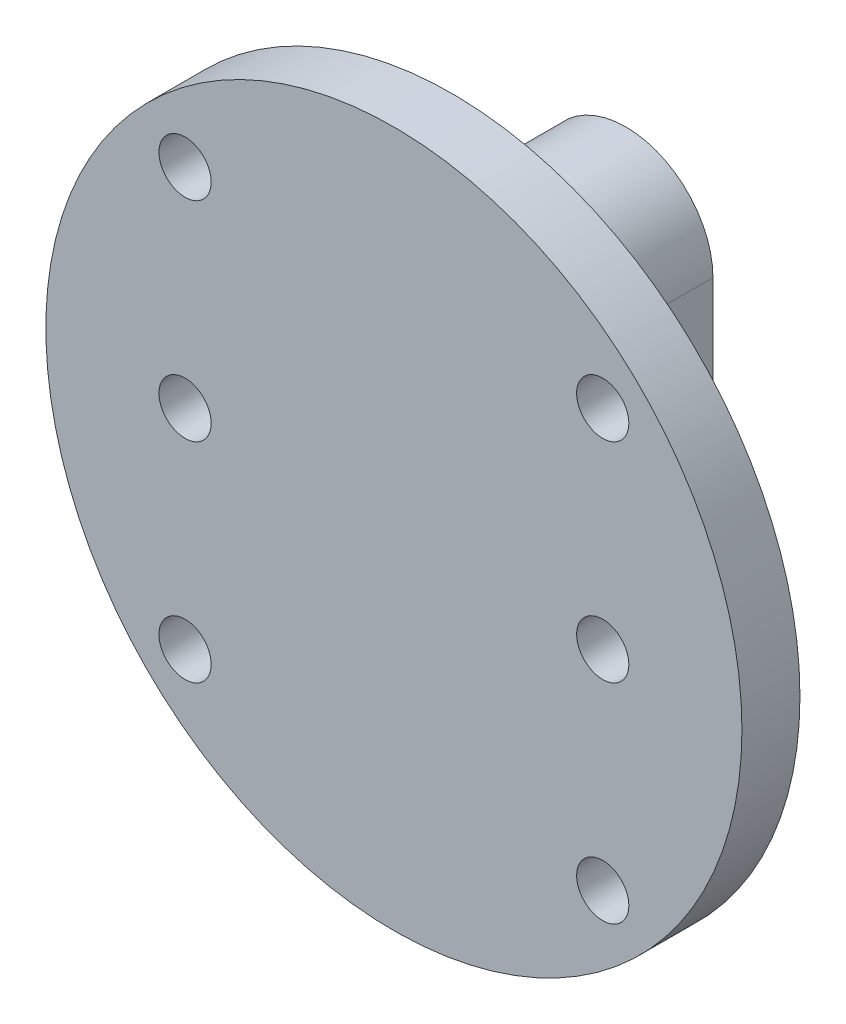
SolidWorks part; units mm, degrees
ref_plane "Plan de face" through (0, 0, 0) normal (0, 0, 1) x (1, 0, 0)
ref_plane "Plan de dessus" through (0, 0, 0) normal (0, 1, 0) x (1, 0, 0)
ref_plane "Plan de droite" through (0, 0, 0) normal (1, 0, 0) x (0, 0, -1)
sketch "Esquisse1" plane through (0, 0, 0) normal (0, 0, 1) x (1, 0, 0)
  line L0 (18, 0) -> (-18, 0) construction
  line L1 (18, 18) -> (-18, 18) construction
  line L2 (18, 18) -> (18, -18) construction
  line L3 (18, -18) -> (-18, -18) construction
  line L4 (-18, 18) -> (-18, -18) construction
  line L5 (18, 18) -> (-18, -18) construction
  line L6 (18, -18) -> (-18, 18) construction
  circle A0 centre (0, 0) radius 30
  circle A2 centre (18, 18) radius 2.25
  circle A3 centre (-18, 18) radius 2.25
  circle A4 centre (-18, -18) radius 2.25
  circle A5 centre (18, -18) radius 2.25
  circle A8 centre (18, 0) radius 2.25
  circle A9 centre (-18, 0) radius 2.25
  point P14 (0, 0)
  point P16 (18, 0)
  dimension "D1" = 60
  dimension "D2" = 4.5
  dimension "D3" = 4.5
  dimension "D4" = 36
  dimension "D5" = 36
extrude "Boss.-Extru.1" add sketch "Esquisse1" along normal blind 5
sketch "Esquisse2" plane through (0, 0, 0) normal (0, 0, -1) x (-1, 0, 0)
  line L0 (0, 12.5) -> (0, -12.5) construction
  line L3 (7.5, 12.5) -> (7.5, -12.5)
  line L4 (-7.5, 12.5) -> (-7.5, -12.5)
  arc A4 (7.5, 12.5) -> (-7.5, 12.5) centre (0, 12.5) ccw
  arc A5 (-7.5, -12.5) -> (7.5, -12.5) centre (0, -12.5) ccw
  circle A6 centre (0, 12.5) radius 2.8
  circle A7 centre (0, -12.5) radius 2.8
  point P3 (0, 0)
  dimension "D1" = 15
  dimension "D2" = 25
  dimension "D3" = 5.6
extrude "Boss.-Extru.2" add sketch "Esquisse2" along normal blind 15
